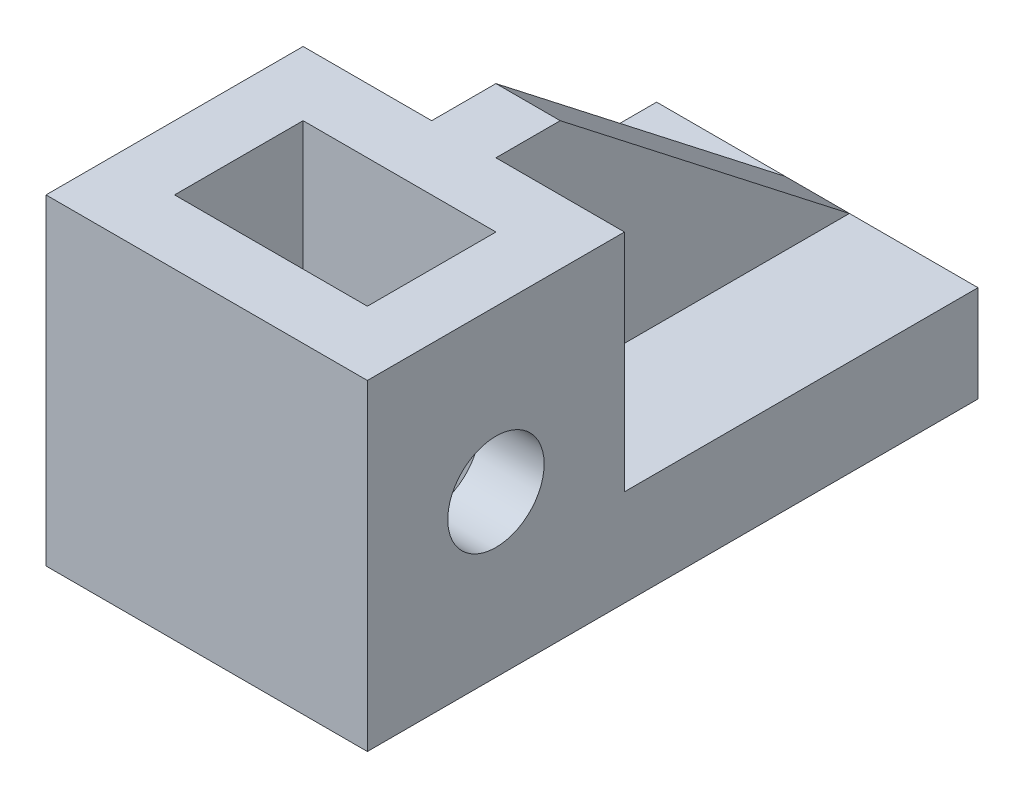
SolidWorks part; units mm, degrees
ref_plane "Front Plane" through (0, 0, 0) normal (0, 0, 1) x (1, 0, 0)
ref_plane "Top Plane" through (0, 0, 0) normal (0, 1, 0) x (1, 0, 0)
ref_plane "Right Plane" through (0, 0, 0) normal (1, 0, 0) x (0, 0, -1)
sketch "Sketch2" plane through (0, 0, 0) normal (1, 0, 0) x (0, 0, -1)
  line L1 (0, 50) -> (40, 50)
  line L2 (0, 50) -> (0, 0)
  line L4 (40, 50) -> (40, 15)
  line L5 (0, 50) -> (40, 0) construction
  line L6 (0, 0) -> (40, 50) construction
  line L7 (95, 0) -> (95, 15)
  line L8 (95, 15) -> (40, 15)
  line L9 (0, 0) -> (95, 0)
  circle A0 centre (20, 25) radius 7.5
  point P0 (20, 25)
  dimension "D5" = 15
  dimension "D1" = 50
  dimension "D2" = 40
  dimension "D3" = 95
  dimension "D4" = 15
extrude "Boss-Extrude1" add sketch "Sketch2" against normal mid plane 50
sketch "Sketch3" plane through (0, 50, 0) normal (0, 1, 0) x (1, 0, 0)
  line L0 (-25, 40) -> (-25, 0) construction
  line L1 (-15, 30) -> (15, 30)
  line L2 (-15, 30) -> (-15, 10)
  line L3 (-15, 10) -> (15, 10)
  line L4 (15, 30) -> (15, 10)
  line L5 (-15, 30) -> (15, 10) construction
  line L6 (-15, 10) -> (15, 30) construction
  line L8 (-25, 0) -> (25, 0) construction
  point P0 (0, 20)
  dimension "D1" = 20
  dimension "D2" = 30
  dimension "D3" = 10
  dimension "D4" = 10
extrude "Cut-Extrude1" cut sketch "Sketch3" against normal blind 40 and the other way through all
sketch "Sketch4" plane through (0, 50, 0) normal (0, 1, 0) x (1, 0, 0)
  line L0 (0, -5.6923) -> (0, 98.5726) construction
  line L1 (-5, 40) -> (-5, 50)
  line L2 (-25, 40) -> (25, 40) construction
  line L3 (-5, 50) -> (5, 50)
  line L4 (5, 50) -> (5, 40)
  line L5 (-25, 40) -> (25, 40) construction
  line L7 (-5, 40) -> (5, 40)
  line L8 (-25, 0) -> (25, 0) construction
  dimension "D1" = 10
  dimension "D3" = 50
extrude "Boss-Extrude2" add sketch "Sketch4" against normal blind 40
sketch "Sketch12" plane through (0, 0, 0) normal (1, 0, 0) x (0, 0, -1)
  line L0 (50, 50) -> (95, 15)
  line L1 (50, 15) -> (50, 50) construction
  line L2 (95, 15) -> (40, 15) construction
  line L3 (95, 0) -> (95, 15) construction
  dimension "D1" = 0
  dimension "D2" = 0
rib "Rib36" sketch "Sketch12" sketch "Sketch12" thickness 10 extrusion direction parallel to sketch draft on no parameters "D1"=10
